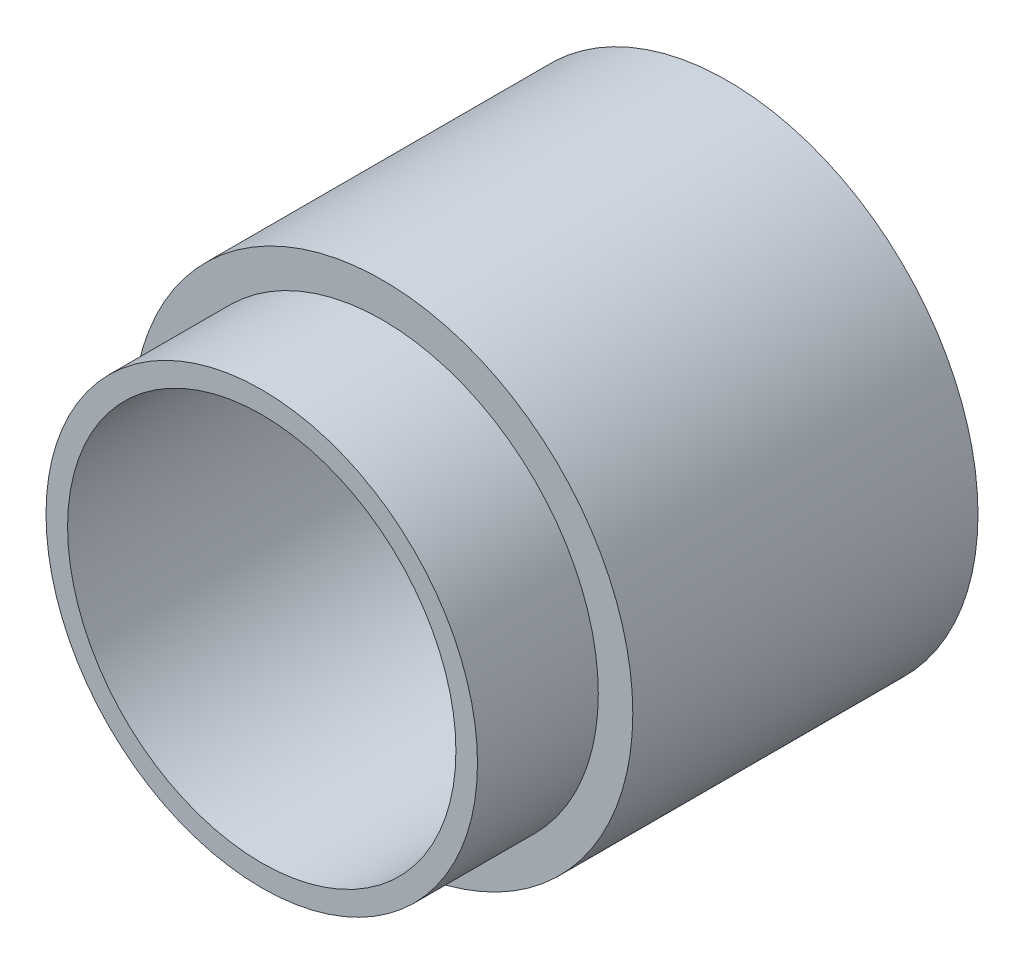
SolidWorks part; units mm, degrees
material "ABS"
ref_plane "Front" through (0, 0, 0) normal (0, 0, 1) x (1, 0, 0)
ref_plane "Top" through (0, 0, 0) normal (0, 1, 0) x (1, 0, 0)
ref_plane "Right" through (0, 0, 0) normal (1, 0, 0) x (0, 0, -1)
sketch "Sketch1" plane through (0, 0, 0) normal (0, 0, 1) x (1, 0, 0)
  circle A0 centre (0, 0) radius 14.5
  dimension "D1" = 29
extrude "Boss-Extrude1" add sketch "Sketch1" along normal mid plane 27
sketch "Sketch2" plane through (0, 0, 13.5) normal (0, 0, 1) x (1, 0, 0)
  circle A0 centre (0, 0) radius 12.5
  dimension "D1" = 25
extrude "Cut-Extrude1" cut sketch "Sketch2" against normal blind 7 flip side to cut
sketch "Sketch3" plane through (0, 0, 13.5) normal (0, 0, 1) x (1, 0, 0)
  circle A0 centre (0, 0) radius 11.25
  dimension "D1" = 22.5
extrude "Cut-Extrude2" cut sketch "Sketch3" against normal through all
